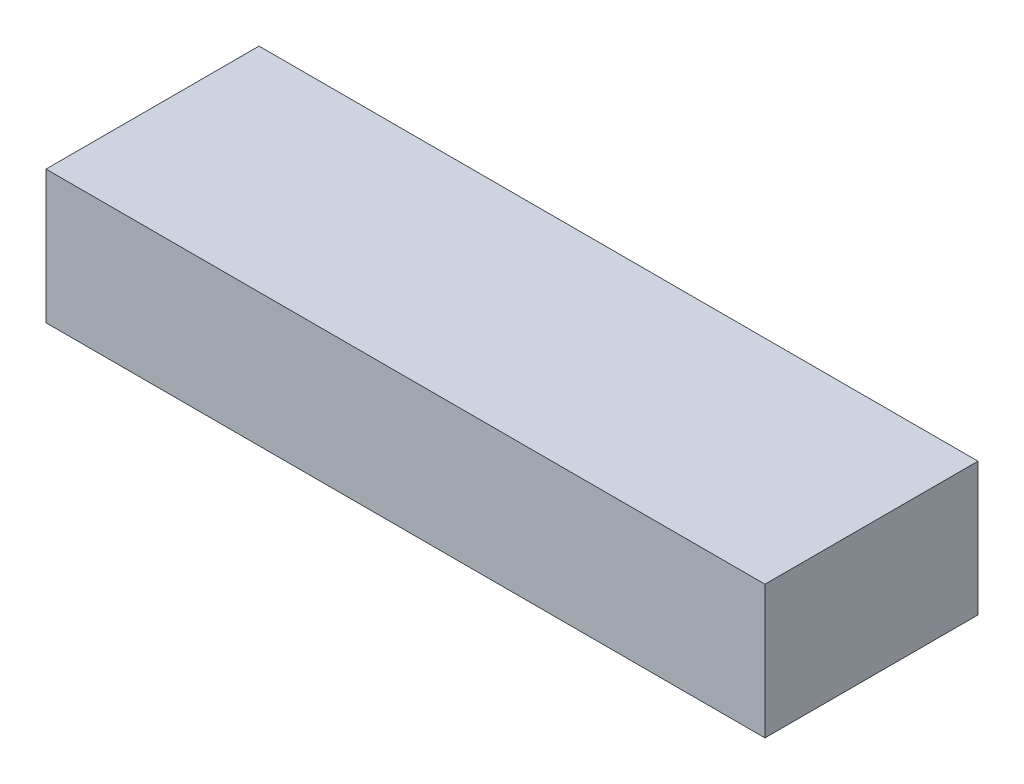
SolidWorks part; units mm, degrees
material "Custom Plastic"
ref_plane "Front Plane" through (0, 0, 0) normal (0, 0, 1) x (1, 0, 0)
ref_plane "Top Plane" through (0, 0, 0) normal (0, 1, 0) x (1, 0, 0)
ref_plane "Right Plane" through (0, 0, 0) normal (1, 0, 0) x (0, 0, -1)
sketch "Sketch1" plane through (0, 0, 0) normal (0, 1, 0) x (1, 0, 0)
  line L1 (-47.8481, 37.9367) -> (87.1519, 37.9367)
  line L2 (-47.8481, 37.9367) -> (-47.8481, -2.0633)
  line L3 (-47.8481, -2.0633) -> (87.1519, -2.0633)
  line L4 (87.1519, 37.9367) -> (87.1519, -2.0633)
  dimension "D1" = 135
  dimension "D2" = 40
extrude "Boss-Extrude1" add sketch "Sketch1" along normal blind 25
